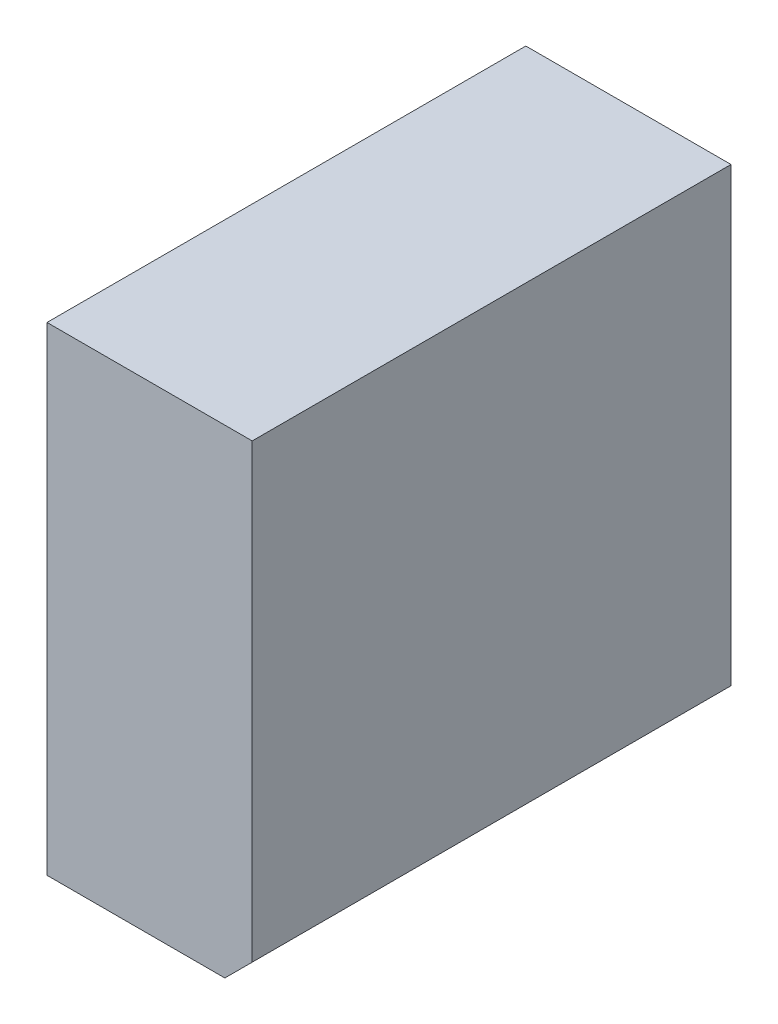
SolidWorks part; units mm, degrees
ref_plane "Front Plane" through (0, 0, 0) normal (0, 0, 1) x (1, 0, 0)
ref_plane "Top Plane" through (0, 0, 0) normal (0, 1, 0) x (1, 0, 0)
ref_plane "Right Plane" through (0, 0, 0) normal (1, 0, 0) x (0, 0, -1)
sketch "Sketch1" plane through (0, 0, 0) normal (0, 0, 1) x (1, 0, 0)
  line L1 (0, 0) -> (38.1, 0)
  line L2 (0, 0) -> (0, 88.9)
  line L3 (0, 88.9) -> (38.1, 88.9)
  line L4 (38.1, 0) -> (38.1, 88.9)
  dimension "D1" = 88.9
  dimension "D2" = 38.1
extrude "Boss-Extrude1" add sketch "Sketch1" along normal blind 88.9
chamfer "Chamfer1" distance 5.08 angle 45 1 edges at (38.1, 0, 44.45)
